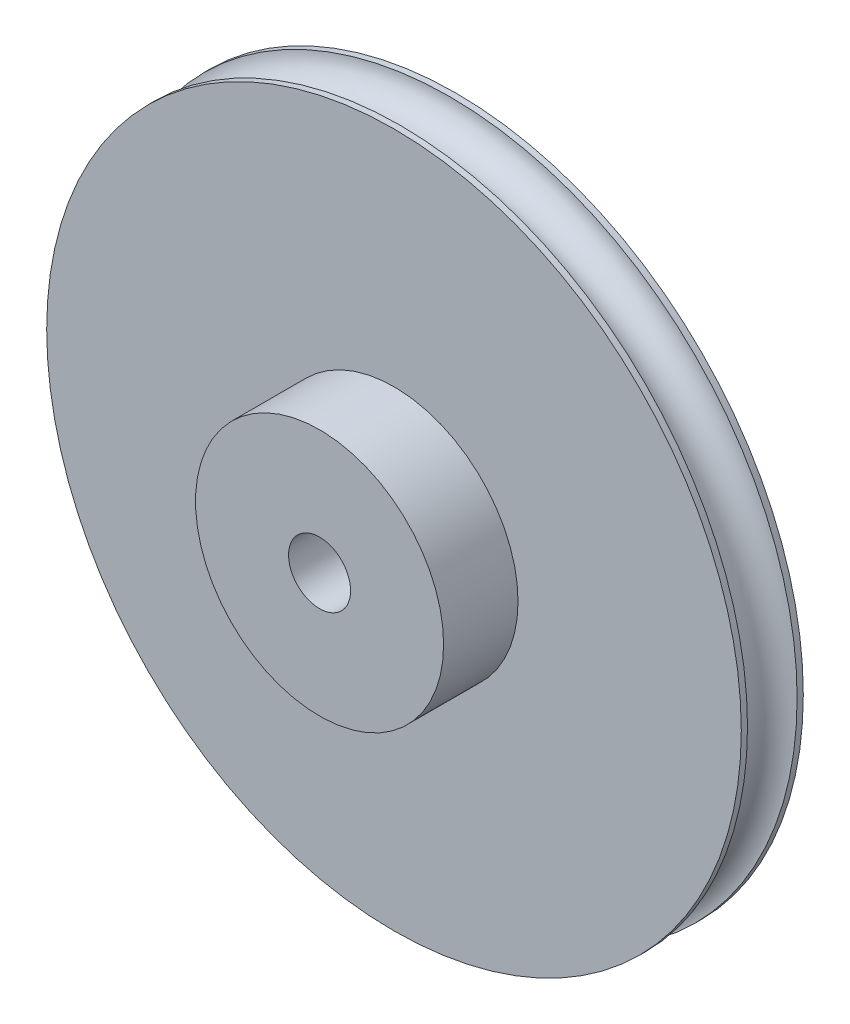
SolidWorks part; units mm, degrees
ref_plane "Plan de face" through (0, 0, 0) normal (0, 0, 1) x (1, 0, 0)
ref_plane "Plan de dessus" through (0, 0, 0) normal (0, 1, 0) x (1, 0, 0)
ref_plane "Plan de droite" through (0, 0, 0) normal (1, 0, 0) x (0, 0, -1)
sketch "Esquisse1" plane through (0, 0, 0) normal (0, 0, 1) x (1, 0, 0)
  circle A0 centre (0, 0) radius 28
  dimension "D1" = 56
extrude "Boss.-Extru.1" add sketch "Esquisse1" along normal blind 5
sketch "Esquisse2" plane through (0, 0, 5) normal (0, 0, 1) x (1, 0, 0)
  circle A0 centre (0, 0) radius 10
  dimension "D1" = 20
extrude "Boss.-Extru.2" add sketch "Esquisse2" along normal blind 6
sketch "Esquisse3" plane through (0, 0, 11) normal (0, 0, 1) x (1, 0, 0)
  circle A0 centre (0, 0) radius 2.5
  dimension "D1" = 5
extrude "Enlèv. mat.-Extru.1" cut sketch "Esquisse3" against normal through all
sketch "Esquisse4" plane through (0, 0, 0) normal (1, 0, 0) x (0, 0, -1)
  line L0 (-2.5, 28) -> (-2.5, 8.0945) construction
  line L1 (0, 28) -> (-5, 28) construction
  line L2 (0, 0) -> (-21.8888, 0) construction
  circle A1 centre (-2.5, 28) radius 2
  dimension "D1" = 4
revolve "Enlèvement de matière-Révolution1" cut sketch "Esquisse4" angle 360 about L2
sketch "Esquisse5" plane through (0, 0, 0) normal (0, 0, -1) x (-1, 0, 0)
  line L0 (0, 0) -> (0, -28)
  line L1 (0, -28) -> (15.3019, -28)
  line L2 (15.3019, -28) -> (-9.8853, -28)
  circle A0 centre (0, 0) radius 28 construction
sketch "Esquisse6" plane through (0, 0, 0) normal (1, 0, 0) x (0, 0, -1)
  line L0 (0, -28) -> (4.7745, -28)
  line L1 (0, 0) -> (0, -28) construction
